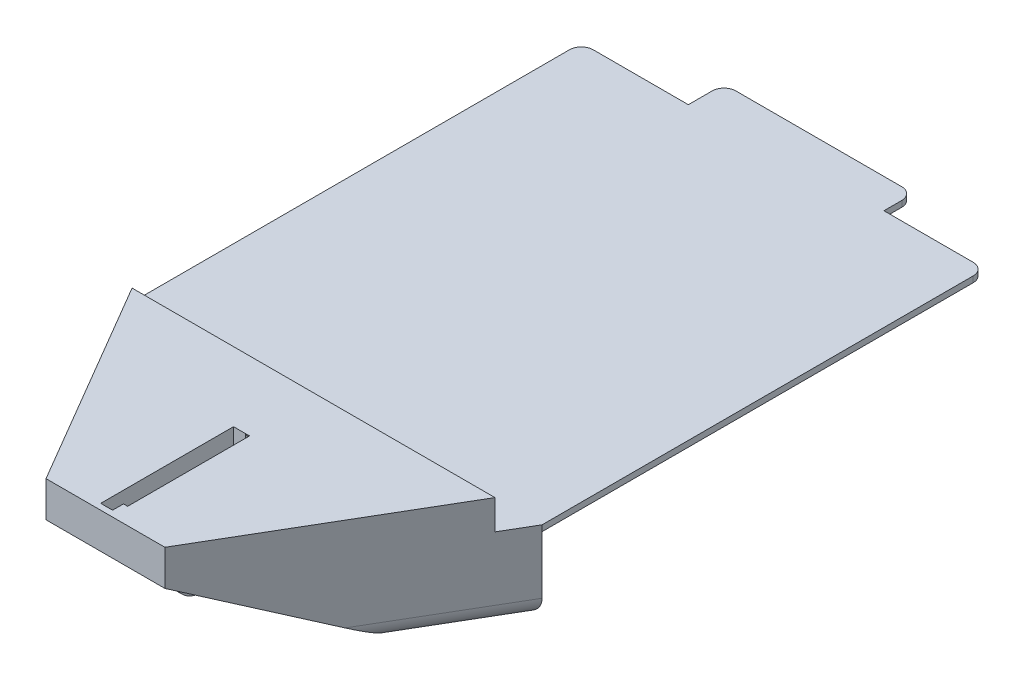
SolidWorks part; units mm, degrees
ref_plane "Front Plane" through (0, 0, 0) normal (0, 0, 1) x (1, 0, 0)
ref_plane "Top Plane" through (0, 0, 0) normal (0, 1, 0) x (1, 0, 0)
ref_plane "Right Plane" through (0, 0, 0) normal (1, 0, 0) x (0, 0, -1)
sketch "Sketch1" plane through (0, 0, 0) normal (0, 1, 0) x (1, 0, 0)
  line L0 (0, 0) -> (-16.35, 0)
  line L1 (-16.35, 0) -> (-16.35, -9.85)
  line L2 (-16.35, -9.85) -> (-2.6, -9.85)
  line L3 (-20.1, -33) -> (-20.1, -75)
  line L4 (-20.1, -75) -> (0, -75)
  line L5 (0, -75) -> (0, 0)
  line L6 (-2.6, -9.85) -> (-2.6, -33)
  line L7 (-2.6, -33) -> (-20.1, -33)
  dimension "D1" = 16.35
  dimension "D2" = 9.85
  dimension "D3" = 13.75
  dimension "D4" = 3.75
  dimension "D5" = 23.15
  dimension "D6" = 42
extrude "Boss-Extrude1" add sketch "Sketch1" along normal blind 7.7
sketch "Sketch2" plane through (0, 0, 75) normal (0, 0, 1) x (1, 0, 0)
  line L0 (-20.1, 7.7) -> (-20.1, 0) construction
  line L1 (-20.1, 5.1) -> (-13.1, 5.1)
  line L2 (-20.1, 5.1) -> (-20.1, 2)
  line L3 (-20.1, 2) -> (-13.1, 2)
  line L4 (-13.1, 5.1) -> (-13.1, 2)
  line L5 (-20.1, 0) -> (0, 0) construction
  dimension "D1" = 7
  dimension "D2" = 3.1
  dimension "D3" = 2
extrude "Cut-Extrude1" cut sketch "Sketch2" against normal through all
fillet "Fillet1" radius 10 1 edges at (-2.6, 3.85, 33)
sketch "Sketch3" plane through (0, 7.7, 0) normal (0, 1, 0) x (1, 0, 0)
  line L0 (0, 0) -> (0, -75)
  line L1 (0, -75) -> (-33.45, -75)
  line L2 (-33.45, -75) -> (-33.45, 0)
  line L3 (-33.45, 0) -> (0, 0)
  line L4 (0, -75) -> (0, -115)
  line L5 (0, -115) -> (-10, -115)
  line L6 (0, 0) -> (0, 4.5)
  line L7 (-33.45, -75) -> (-10, -115)
  line L8 (0, 4.5) -> (-33.45, 4.5)
  line L9 (-33.45, 4.5) -> (-33.45, 0)
  dimension "D1" = 33.45
  dimension "D2" = 40
  dimension "D3" = 10
  dimension "D4" = 4.5
extrude "Boss-Extrude2" add sketch "Sketch3" along normal blind 6
sketch "Sketch4" plane through (0, 0, 0) normal (1, 0, 0) x (0, 0, -1)
  line L0 (-115, 13.7) -> (-115, 16.7)
  line L1 (-115, 16.7) -> (-100, 16.7)
  line L2 (-100, 16.7) -> (-55.25, 13.7)
  line L3 (-115, 13.7) -> (4.5, 13.7) construction
  line L4 (-115, 13.7) -> (-55.25, 13.7)
  point P8 (-55.25, 13.7)
  dimension "D1" = 15
  dimension "D2" = 3
extrude "Boss-Extrude3" [suppressed] add sketch "Sketch4" against normal up to surface (33.45 mm away)
sketch "Sketch5" plane through (-33.45, 0, 0) normal (-1, 0, 0) x (0, 0, 1)
  line L0 (75, 7.7) -> (75, -5)
  line L1 (75, -5) -> (90, -5)
  line L2 (90, -5) -> (115, 7.7)
  line L3 (115, 7.7) -> (75, 7.7)
  line L4 (33, 0) -> (75, 0) construction
  dimension "D1" = 5
  dimension "D2" = 15
extrude "Boss-Extrude4" add sketch "Sketch5" against normal up to surface (33.45 mm away) up to face at (0, 7.275, 46.375)
sketch "Sketch6" plane through (0, 7.7, 0) normal (0, 1, 0) x (1, 0, 0)
  line L0 (-33.45, -75) -> (-10, -115)
  line L1 (-10, -115) -> (-33.45, -115)
  line L2 (-33.45, -115) -> (-33.45, -75)
extrude "Cut-Extrude2" cut sketch "Sketch6" against normal through all both and the other way through all
sketch "Sketch7" plane through (0, 0, 0) normal (1, 0, 0) x (0, 0, -1)
  line L0 (-75, 0) -> (-82, 0)
  line L1 (-82, 0) -> (-80, -5)
  line L2 (-90, -5) -> (-75, -5) construction
  line L3 (-80, -5) -> (-75, -5)
  line L4 (-75, -5) -> (-75, 0)
  dimension "D1" = 5
  dimension "D2" = 7
extrude "Cut-Extrude3" cut sketch "Sketch7" against normal blind 10
fillet "Fillet3" radius 1 2 edges at (-5, -5, 80) (-10, -5, 77.5)
fillet "Fillet4" [suppressed] radius 5
mirror "Mirror1" about plane through (0, 7.7, 75) normal (-1, 0, 0) of bodies 110
fillet "Fillet5" radius 3 2 edges at (-29.0531, -5, 82.5) (29.0531, -5, 82.5)
sketch "Sketch8" plane through (0, 13.7, 0) normal (0, 1, 0) x (1, 0, 0)
  line L0 (33.45, 4.5) -> (33.45, -0.5)
  line L1 (33.45, -75) -> (33.45, 4.5) construction
  line L2 (33.45, -0.5) -> (16.45, -0.5)
  line L3 (16.45, -0.5) -> (16.45, 4.5)
  line L4 (33.45, 4.5) -> (-33.45, 4.5) construction
  line L5 (16.45, 4.5) -> (33.45, 4.5)
  line L6 (0, 37.0905) -> (0, -37.0905) construction
  line L7 (-16.45, -0.5) -> (-16.45, 4.5) construction
  line L8 (-33.45, -0.5) -> (-16.45, -0.5) construction
  line L9 (-33.45, 4.5) -> (-33.45, -0.5) construction
  line L10 (-16.45, 4.5) -> (-33.45, 4.5) construction
  line L11 (-15.45, -1.5) -> (-15.45, 5.5)
  line L12 (-15.45, 5.5) -> (-34.45, 5.5)
  line L13 (-34.45, 5.5) -> (-34.45, -1.5)
  line L14 (-34.45, -1.5) -> (-15.45, -1.5)
  point P13 (0, 0)
  dimension "D1" = 5
  dimension "D2" = 17
  dimension "D3" = 1
extrude "Cut-Extrude4" cut sketch "Sketch8" against normal up to surface (13.7 mm away) up to face at (0, 0, 38.0857)
fillet "Fillet6" radius 2 2 edges at (-15.45, 10.7, -4.5) (-33.45, 10.7, 1.5)
fillet "Fillet7" radius 2 2 edges at (33.45, 10.7, 0.5) (16.45, 10.7, -4.5)
ref_plane "Plane1" through (0.2, 0, 0) normal (-1, 0, 0) x (0, 0, 1)
sketch "Sketch11" plane through (0.2, 0, 0) normal (-1, 0, 0) x (0, 0, 1)
  line L0 (82.4909, -1.3) -> (93.4909, 16.7)
  line L1 (82.4909, -1.3) -> (103, -1.3)
  line L2 (93.4909, 16.7) -> (114, 16.7)
  line L3 (103, -1.3) -> (114, 16.7)
  line L4 (75, 13.7) -> (115, 13.7) construction
  line L5 (115, 13.7) -> (115, 7.7) construction
  circle A0 centre (103, -1.3) radius 1
  circle A1 centre (82.4909, -1.3) radius 1
  dimension "D6" = 2
  dimension "D7" = 2
  dimension "D1" = 18
  dimension "D2" = 17.5
  dimension "D3" = 11
  dimension "D4" = 3
  dimension "D5" = 1
sketch "Sketch12" plane through (0.2, 0, 0) normal (-1, 0, 0) x (0, 0, 1)
  line L2 (93.3465, -3.3) -> (108.9728, 4.6382)
  line L3 (95.9055, -2) -> (115, 7.7) construction
  line L4 (104.1217, -3.3) -> (115.7066, 15.6571)
  line L5 (82.4909, -3.3) -> (104.1217, -3.3)
  line L6 (104.1217, -3.3) -> (108.9728, 4.6382)
  line L7 (93.3465, -3.3) -> (104.1217, -3.3)
  line L8 (90, -5) -> (95.9055, -2) construction
  dimension "D1" = 2
extrude "Boss-Extrude5" add sketch "Sketch12" along normal mid plane 5
fillet "Fillet8" radius 5 1 edges at (0.2, -3.3, 104.1217)
extrude "Cut-Extrude5" cut sketch "Sketch11" against normal blind 0.7 contours A1 L1 A0 L3 L2 L0 | L0 A1 L1 | L1 A1 L0 | L3 A0 L1 | L1 A0 L3
sketch "Sketch13" plane through (0.2, 0, 0) normal (-1, 0, 0) x (0, 0, 1)
  line L0 (75, 13.7) -> (115, 13.7) construction
  line L1 (114, 13.7) -> (91.6576, 13.7)
  line L2 (114, 13.7) -> (114, 9.7)
  line L3 (114, 9.7) -> (91.6576, 9.7)
  line L4 (91.6576, 13.7) -> (91.6576, 9.7)
  line L5 (82.4909, -1.3) -> (93.4909, 16.7) construction
  dimension "D1" = 4
extrude "Cut-Extrude6" cut sketch "Sketch13" along normal blind 2
sketch "Sketch14" plane through (0, 13.7, 0) normal (0, 1, 0) x (1, 0, 0)
  line L0 (-33.45, -75) -> (-33.45, -3.5) construction
  line L1 (33.45, 4.5) -> (-33.45, 4.5)
  line L2 (33.45, 4.5) -> (33.45, -80)
  line L3 (33.45, -80) -> (-33.45, -80)
  line L4 (-33.45, 4.5) -> (-33.45, -80)
  line L5 (20.1, -75) -> (33.45, -75) construction
  line L6 (33.45, -75) -> (33.45, -2.5) construction
  line L7 (14.45, 4.5) -> (-13.45, 4.5) construction
  dimension "D1" = 5
extrude "Cut-Extrude8" cut sketch "Sketch14" against normal blind 5
